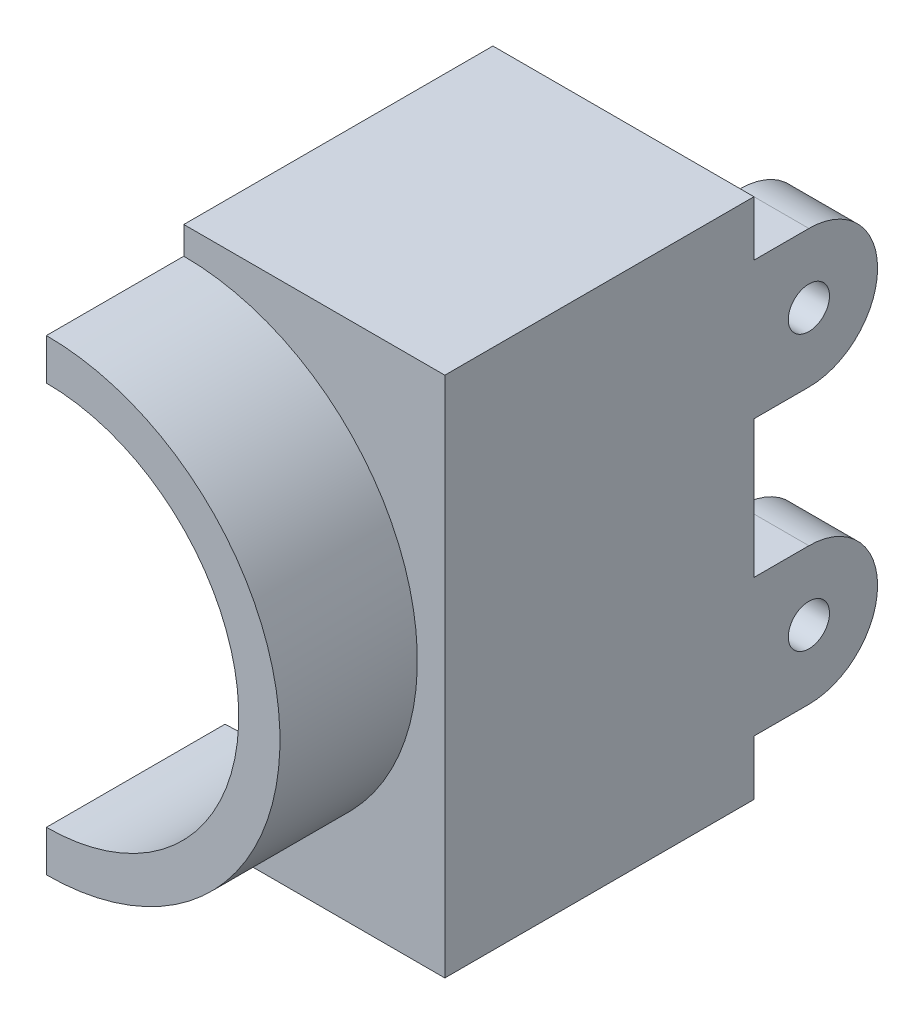
SolidWorks part; units mm, degrees
material "ABS"
ref_plane "前视基准面" through (0, 0, 0) normal (0, 0, 1) x (1, 0, 0)
ref_plane "上视基准面" through (0, 0, 0) normal (0, 1, 0) x (1, 0, 0)
ref_plane "右视基准面" through (0, 0, 0) normal (1, 0, 0) x (0, 0, -1)
sketch "草图1" plane through (0, 0, 0) normal (0, 0, 1) x (1, 0, 0)
  circle A0 centre (0, 0) radius 14
  circle A1 centre (0, 0) radius 17
  dimension "D1" = 28
  dimension "D2" = 34
extrude "凸台-拉伸1" add sketch "草图1" along normal blind 10
sketch "草图2" plane through (0, 0, 0) normal (0, 0, -1) x (-1, 0, 0)
  line L1 (19, 19) -> (-19, 19)
  line L2 (19, 19) -> (19, -19)
  line L3 (19, -19) -> (-19, -19)
  line L4 (-19, 19) -> (-19, -19)
  line L5 (0, -19) -> (0, 19) construction
  line L6 (19, 0) -> (-19, 0) construction
  point P0 (0, 0)
  dimension "D1" = 38
  dimension "D2" = 38
extrude "凸台-拉伸2" add sketch "草图2" along normal blind 22.5
sketch "草图3" plane through (0, 0, -22.5) normal (0, 0, -1) x (-1, 0, 0)
  line L1 (16, 16) -> (-16, 16)
  line L2 (16, 16) -> (16, -16)
  line L3 (16, -16) -> (-16, -16)
  line L4 (-16, 16) -> (-16, -16)
  line L5 (0, -16) -> (0, 16) construction
  line L6 (16, 0) -> (-16, 0) construction
  point P0 (0, 0)
  dimension "D1" = 32
  dimension "D2" = 32
extrude "切除-拉伸1" cut sketch "草图3" against normal blind 19.5
sketch "草图4" plane through (0, 0, 0) normal (0, 0, 1) x (1, 0, 0)
  circle A1 centre (0, 0) radius 14
  circle A2 centre (0, 0) radius 14
  dimension "D1" = 0
extrude "切除-拉伸2" cut sketch "草图4" against normal through all
sketch "草图5" plane through (0, 0, -22.5) normal (0, 0, -1) x (-1, 0, 0)
  line L1 (-4.5, -16) -> (7.6, -16)
  line L2 (-4.5, -16) -> (-4.5, -4.84)
  line L3 (-4.5, -4.84) -> (7.6, -4.84)
  line L4 (-19, 19) -> (-19, -19)
  line L5 (-19, -19) -> (19, -19)
  line L6 (19, -19) -> (19, 19)
  line L7 (19, 19) -> (-19, 19)
  line L8 (-19, 19) -> (-19, -19)
  line L9 (-19, -19) -> (19, -19)
  line L10 (19, -19) -> (19, 19)
  line L11 (19, 19) -> (-19, 19)
  line L12 (7.6, -16) -> (7.6, -4.84)
  line L13 (-16, 16) -> (-16, -16) construction
  line L15 (16, -16) -> (16, 16) construction
  line L16 (-16, -16) -> (16, -16) construction
  line L17 (-16, -16) -> (16, -16) construction
  dimension "D2" = 11.5
  dimension "D3" = 8.4
  dimension "D4" = 11.16
  dimension "D1" = 0
extrude "凸台-拉伸3" add sketch "草图5" against normal blind 3
sketch "草图6" plane through (0, 0, 0) normal (1, 0, 0) x (0, 0, -1)
  line L0 (22.5, 4.5) -> (25.5, 4.5)
  line L1 (22.5, 19) -> (22.5, -19) construction
  line L2 (25.5, -4.5) -> (22.5, -4.5)
  line L3 (22.5, -4.5) -> (22.5, 4.5)
  arc A0 (25.5, 4.5) -> (25.5, -4.5) centre (25.5, 0) cw
  circle A1 centre (25.5, 0) radius 1.5
  dimension "D3" = 3
  dimension "D1" = 3
  dimension "D2" = 9
extrude "凸台-拉伸4" add sketch "草图6" along normal mid plane 6
sketch "草图7" plane through (19, 0, 0) normal (1, 0, 0) x (0, 0, -1)
  line L0 (22.5, 15) -> (26.5, 15)
  line L1 (22.5, 19) -> (22.5, -19) construction
  line L2 (26.5, 5) -> (22.5, 5)
  line L3 (22.5, 5) -> (22.5, 15)
  line L4 (-15.6353, 0) -> (39.5425, 0) construction
  line L5 (22.5, -5) -> (22.5, -15)
  line L6 (26.5, -5) -> (22.5, -5)
  line L7 (22.5, -15) -> (26.5, -15)
  arc A0 (26.5, 15) -> (26.5, 5) centre (26.5, 10) cw
  circle A1 centre (26.5, 10) radius 1.5
  circle A2 centre (26.5, -10) radius 1.5
  arc A3 (26.5, -15) -> (26.5, -5) centre (26.5, -10) ccw
  dimension "D1" = 3
  dimension "D3" = 5
  dimension "D2" = 10
  dimension "D4" = 4
extrude "凸台-拉伸5" add sketch "草图7" against normal blind 5
sketch "草图8" plane through (14, 0, 0) normal (-1, 0, 0) x (0, 0, 1)
  line L0 (-46.7529, 0) -> (17.6956, 0) construction
  line L1 (-26.5, 6.8246) -> (-23.75, 8.4123)
  line L2 (-23.75, 8.4123) -> (-23.75, 11.5877)
  line L3 (-23.75, 11.5877) -> (-26.5, 13.1754)
  line L4 (-26.5, 13.1754) -> (-29.25, 11.5877)
  line L5 (-29.25, 11.5877) -> (-29.25, 8.4123)
  line L6 (-29.25, 8.4123) -> (-26.5, 6.8246)
  line L7 (-29.25, -8.4123) -> (-26.5, -6.8246)
  line L8 (-29.25, -11.5877) -> (-29.25, -8.4123)
  line L9 (-26.5, -13.1754) -> (-29.25, -11.5877)
  line L10 (-23.75, -11.5877) -> (-26.5, -13.1754)
  line L11 (-23.75, -8.4123) -> (-23.75, -11.5877)
  line L12 (-26.5, -6.8246) -> (-23.75, -8.4123)
  circle A0 centre (-26.5, 10) radius 2.75 construction
  circle A1 centre (-26.5, -10) radius 2.75 construction
  dimension "D1" = 5.5
extrude "切除-拉伸3" cut sketch "草图8" against normal blind 2
mirror "镜向1" about plane through (0, 0, 0) normal (1, 0, 0) of "凸台-拉伸5", "切除-拉伸3"
sketch "草图9" plane through (0, 0, -22.5) normal (0, 0, -1) x (-1, 0, 0)
  line L1 (0, 27.5974) -> (31.8568, 27.5974)
  line L2 (0, 27.5974) -> (0, -27.9906)
  line L3 (0, -27.9906) -> (31.8568, -27.9906)
  line L4 (31.8568, 27.5974) -> (31.8568, -27.9906)
extrude "切除-拉伸5" cut sketch "草图9" against normal through all and the other way through all contours L4 L3 L2 L1
